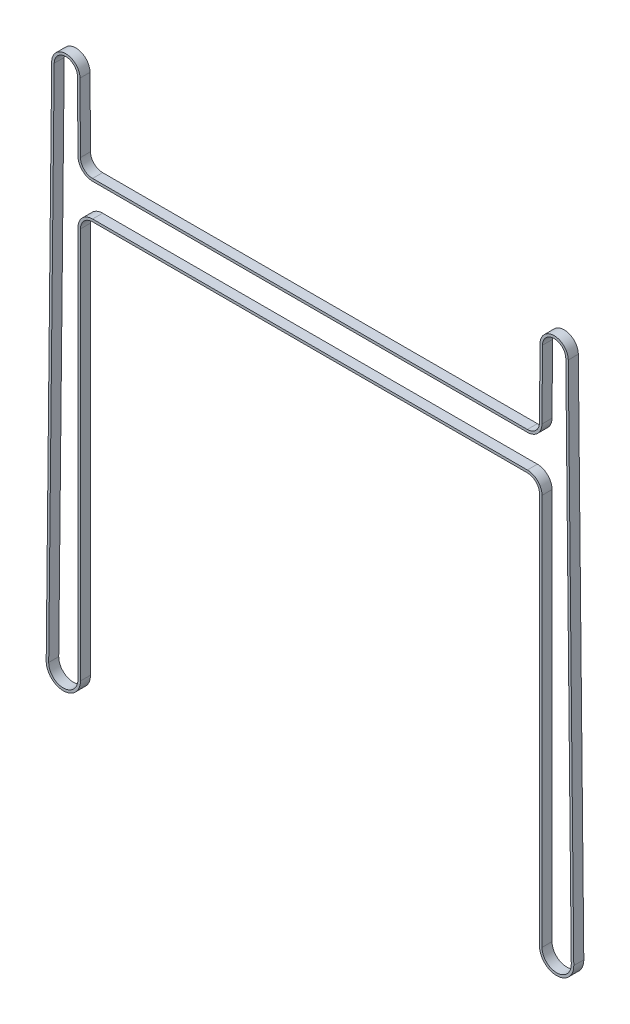
SolidWorks part; units mm, degrees
material "Полиуретан (11671)"
ref_plane "Front" through (0, 0, 0) normal (0, 0, 1) x (1, 0, 0)
ref_plane "Top" through (0, 0, 0) normal (0, 1, 0) x (1, 0, 0)
ref_plane "Right" through (0, 0, 0) normal (1, 0, 0) x (0, 0, -1)
sketch "Эскиз2" plane through (0, 0, 0) normal (0, 0, 1) x (1, 0, 0)
  line L0 (0, 0) -> (1, 0) construction
  line L1 (0, 0) -> (0, 1) construction
  line L2 (1.1477, 2.262) -> (4.4336, -309.7192)
  line L3 (-13.0679, -309.8113) -> (-13.0659, -75.6778)
  line L4 (-21.8169, -66.9267) -> (-281.8169, -66.9267)
  line L5 (-290.5679, -75.6778) -> (-290.5659, -309.8113)
  line L6 (-308.0674, -309.7192) -> (-304.7815, 2.262)
  line L7 (-290.8521, 2.237) -> (-290.5677, -38.7384)
  line L8 (-281.8169, -47.4287) -> (-21.8169, -47.4287)
  line L9 (-13.0661, -38.7384) -> (-12.7817, 2.237)
  arc A0 (-12.7817, 2.237) -> (1.1477, 2.262) centre (-5.8169, 2.1886) cw
  arc A1 (4.4336, -309.7192) -> (-13.0679, -309.8113) centre (-4.3169, -309.8114) cw
  arc A2 (-13.0659, -75.6778) -> (-21.8169, -66.9267) centre (-21.8169, -75.6777) ccw
  arc A3 (-281.8169, -66.9267) -> (-290.5679, -75.6778) centre (-281.8169, -75.6777) ccw
  arc A4 (-290.5659, -309.8113) -> (-308.0674, -309.7192) centre (-299.3169, -309.8114) cw
  arc A5 (-304.7815, 2.262) -> (-290.8521, 2.237) centre (-297.8169, 2.1886) cw
  arc A6 (-290.5677, -38.7384) -> (-281.8169, -47.4287) centre (-281.8169, -38.6777) ccw
  arc A7 (-21.8169, -47.4287) -> (-13.0661, -38.7384) centre (-21.8169, -38.6777) ccw
extrude "Вытянуть-Тонкостенный1" add sketch "Эскиз2" along normal blind 6 thin thin type one direction wall 1.5
